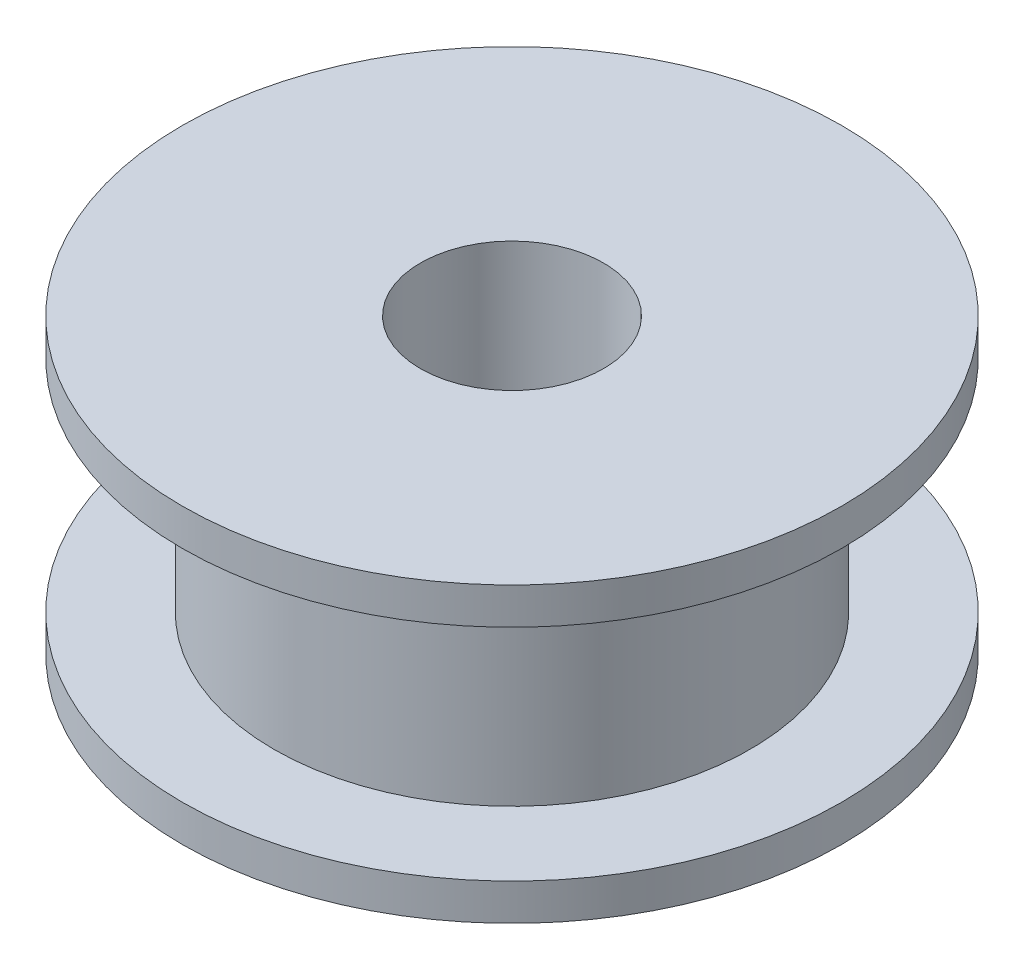
SolidWorks part; units mm, degrees
ref_plane "Front Plane" through (0, 0, 0) normal (0, 0, 1) x (1, 0, 0)
ref_plane "Top Plane" through (0, 0, 0) normal (0, 1, 0) x (1, 0, 0)
ref_plane "Right Plane" through (0, 0, 0) normal (1, 0, 0) x (0, 0, -1)
sketch "Sketch1" plane through (0, 0, 0) normal (0, 1, 0) x (1, 0, 0)
  circle A0 centre (0, 0) radius 9
  circle A1 centre (0, 0) radius 2.5
  dimension "D1" = 18
  dimension "D2" = 5
extrude "Boss-Extrude1" add sketch "Sketch1" along normal blind 1
sketch "Sketch2" plane through (0, 1, 0) normal (0, 1, 0) x (1, 0, 0)
  circle A0 centre (0, 0) radius 2.5
  circle A1 centre (0, 0) radius 6.5
  dimension "D1" = 13
extrude "Boss-Extrude2" add sketch "Sketch2" along normal blind 6
sketch "Sketch3" plane through (0, 7, 0) normal (0, 1, 0) x (1, 0, 0)
  circle A0 centre (0, 0) radius 2.5
  circle A1 centre (0, 0) radius 9
extrude "Boss-Extrude3" add sketch "Sketch3" along normal blind 1
